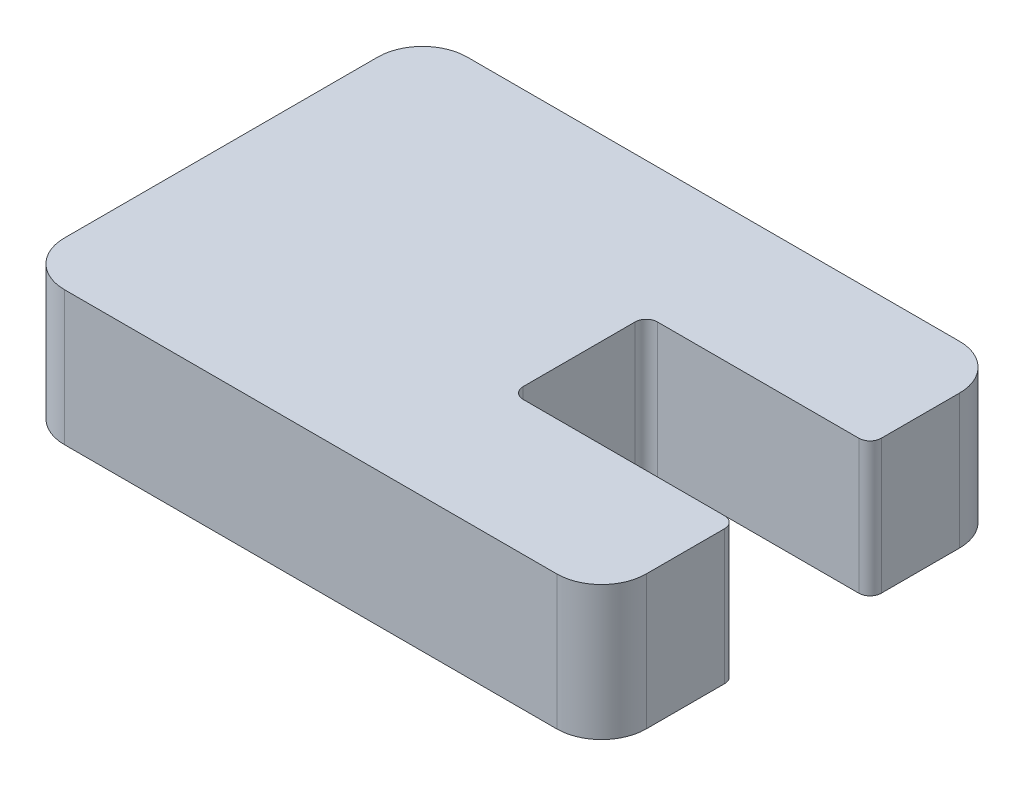
SolidWorks part; units mm, degrees
ref_plane "Alzado" through (0, 0, 0) normal (0, 0, 1) x (1, 0, 0)
ref_plane "Planta" through (0, 0, 0) normal (0, 1, 0) x (1, 0, 0)
ref_plane "Vista lateral" through (0, 0, 0) normal (1, 0, 0) x (0, 0, -1)
sketch "Croquis1" plane through (0, 0, 0) normal (0, 1, 0) x (1, 0, 0)
  line L0 (0, 3.5) -> (0, -3.5)
  line L1 (1, -4.5) -> (12, -4.5)
  line L2 (13, -3.5) -> (13, -1.5)
  line L3 (13, -1.5) -> (8, -1.5)
  line L4 (8, -1.5) -> (8, 1.5)
  line L5 (8, 1.5) -> (13, 1.5)
  line L6 (13, 1.5) -> (13, 3.5)
  line L7 (12, 4.5) -> (1, 4.5)
  arc A0 (12, -4.5) -> (13, -3.5) centre (12, -3.5) ccw
  arc A1 (0, -3.5) -> (1, -4.5) centre (1, -3.5) ccw
  arc A2 (0, 3.5) -> (1, 4.5) centre (1, 3.5) cw
  arc A3 (13, 3.5) -> (12, 4.5) centre (12, 3.5) ccw
  point P4 (0, 0)
  point P12 (13, -4.5)
  point P17 (0, 4.5)
  point P20 (13, 4.5)
  dimension "D7" = 1
  dimension "D8" = 1
  dimension "D1" = 3
  dimension "D2" = 3
  dimension "D3" = 3
  dimension "D4" = 13
  dimension "D5" = 5
  dimension "D6" = 5
extrude "Saliente-Extruir1" add sketch "Croquis1" along normal blind 3
fillet "Redondeo1" radius 0.25 4 edges at (13, 1.5, 1.5) (13, 1.5, -1.5) (8, 1.5, 1.5) (8, 1.5, -1.5)
